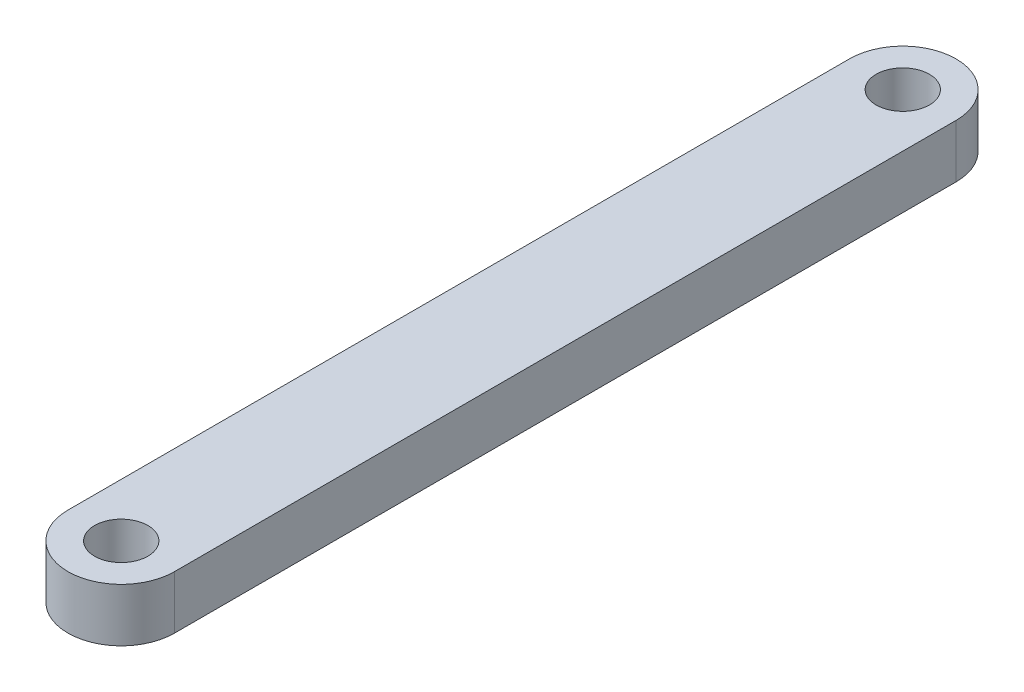
SolidWorks part; units mm, degrees
ref_plane "Plan de face" through (0, 0, 0) normal (0, 0, 1) x (1, 0, 0)
ref_plane "Plan de dessus" through (0, 0, 0) normal (0, 1, 0) x (1, 0, 0)
ref_plane "Plan de droite" through (0, 0, 0) normal (1, 0, 0) x (0, 0, -1)
sketch "Esquisse1" plane through (0, 0, 0) normal (0, 1, 0) x (1, 0, 0)
  line L0 (20.3844, -22) -> (-20.2781, -22) construction
  line L1 (-3, 0) -> (-3, -44)
  line L2 (3, 0) -> (3, -44)
  circle A0 centre (0, 0) radius 1.5
  arc A1 (3, 0) -> (-3, 0) centre (0, 0) ccw
  arc A2 (3, -44) -> (-3, -44) centre (0, -44) cw
  circle A3 centre (0, -44) radius 1.5
  point P10 (3, -22)
  point P11 (-3, -22)
  dimension "D1" = 3
  dimension "D2" = 3
  dimension "D3" = 22
extrude "Boss.-Extru.1" add sketch "Esquisse1" along normal blind 3
